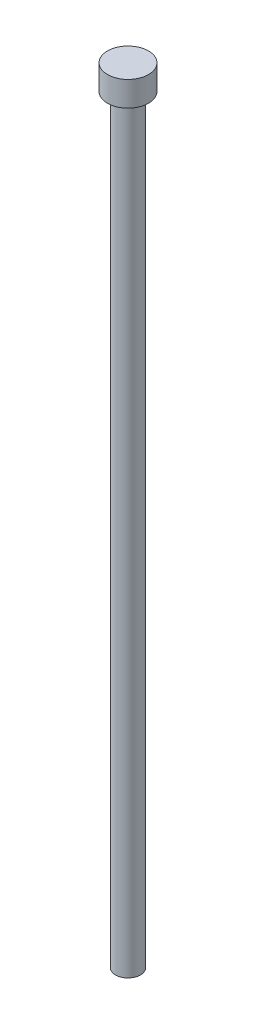
SolidWorks part; units mm, degrees
ref_plane "Front Plane" through (0, 0, 0) normal (0, 0, 1) x (1, 0, 0)
ref_plane "Top Plane" through (0, 0, 0) normal (0, 1, 0) x (1, 0, 0)
ref_plane "Right Plane" through (0, 0, 0) normal (1, 0, 0) x (0, 0, -1)
sketch "Sketch1" plane through (0, 0, 0) normal (0, 1, 0) x (1, 0, 0)
  circle A0 centre (0, 0) radius 3.429
  dimension "D1" = 6.858
extrude "Boss-Extrude1" add sketch "Sketch1" along normal blind 4.1656
sketch "Sketch2" plane through (0, 0, 0) normal (0, -1, 0) x (1, 0, 0)
  circle A0 centre (0, 0) radius 2.0828
  dimension "D1" = 4.1656
extrude "Boss-Extrude2" add sketch "Sketch2" along normal blind 127
